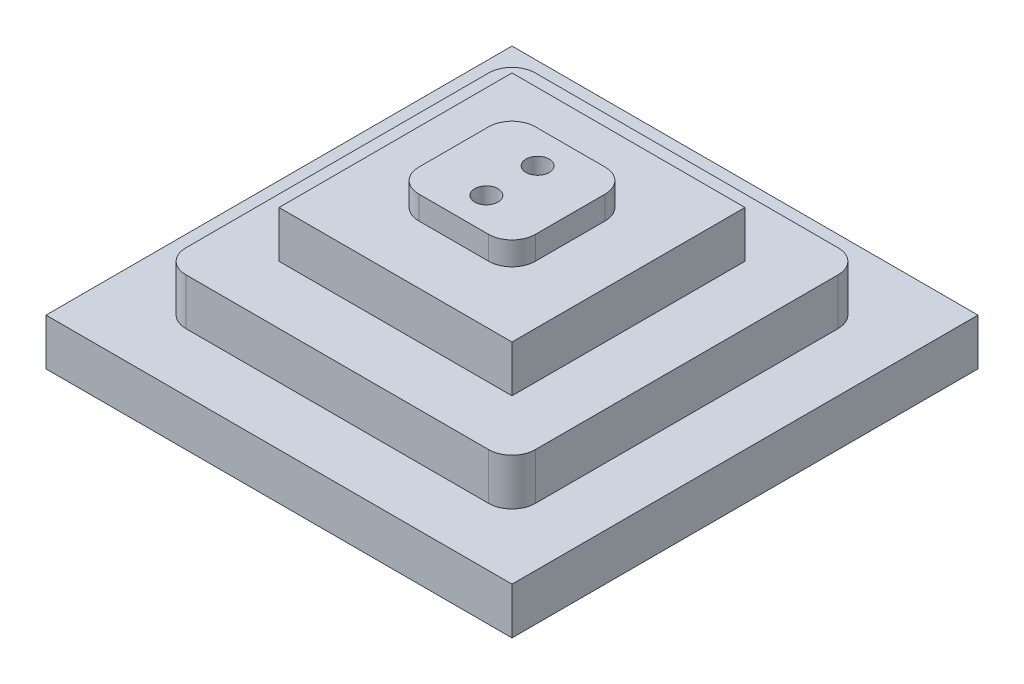
SolidWorks part; units mm, degrees
ref_plane "Front Plane" through (0, 0, 0) normal (0, 0, 1) x (1, 0, 0)
ref_plane "Top Plane" through (0, 0, 0) normal (0, 1, 0) x (1, 0, 0)
ref_plane "Right Plane" through (0, 0, 0) normal (1, 0, 0) x (0, 0, -1)
sketch "Sketch1" plane through (0, 0, 0) normal (0, 1, 0) x (1, 0, 0)
  line L1 (0, 0) -> (100, 0)
  line L2 (0, 0) -> (0, 100)
  line L3 (0, 100) -> (100, 100)
  line L4 (100, 0) -> (100, 100)
  dimension "D1" = 100
  dimension "D2" = 100
extrude "Boss-Extrude1" add sketch "Sketch1" along normal blind 10
sketch "Sketch2" plane through (0, 10, 0) normal (0, 1, 0) x (1, 0, 0)
  line L0 (0, 50) -> (100, 50) construction
  line L1 (0, 100) -> (0, 0) construction
  line L2 (100, 0) -> (100, 100) construction
  line L3 (50, 100) -> (50, 0) construction
  line L4 (100, 100) -> (0, 100) construction
  line L5 (0, 0) -> (100, 0) construction
  line L7 (87.5, 12.5) -> (12.5, 12.5)
  line L8 (87.5, 12.5) -> (87.5, 87.5)
  line L9 (87.5, 87.5) -> (12.5, 87.5)
  line L10 (12.5, 12.5) -> (12.5, 87.5)
  line L11 (87.5, 12.5) -> (12.5, 87.5) construction
  line L12 (87.5, 87.5) -> (12.5, 12.5) construction
  point P12 (50, 50)
  dimension "D1" = 75
  dimension "D2" = 75
extrude "Boss-Extrude2" add sketch "Sketch2" along normal blind 10
sketch "Sketch3" plane through (0, 20, 0) normal (0, 1, 0) x (1, 0, 0)
  line L0 (12.5, 50) -> (87.5, 50) construction
  line L1 (12.5, 87.5) -> (12.5, 12.5) construction
  line L2 (87.5, 12.5) -> (87.5, 87.5) construction
  line L3 (50, 87.5) -> (50, 12.5) construction
  line L4 (87.5, 87.5) -> (12.5, 87.5) construction
  line L5 (12.5, 12.5) -> (87.5, 12.5) construction
  line L7 (75, 25) -> (25, 25)
  line L8 (75, 25) -> (75, 75)
  line L9 (75, 75) -> (25, 75)
  line L10 (25, 25) -> (25, 75)
  line L11 (75, 25) -> (25, 75) construction
  line L12 (75, 75) -> (25, 25) construction
  point P12 (50, 50)
  dimension "D1" = 50
  dimension "D2" = 50
extrude "Boss-Extrude3" add sketch "Sketch3" along normal blind 10
sketch "Sketch4" plane through (0, 30, 0) normal (0, 1, 0) x (1, 0, 0)
  line L0 (25, 50) -> (75, 50) construction
  line L1 (25, 75) -> (25, 25) construction
  line L2 (75, 25) -> (75, 75) construction
  line L3 (50, 75) -> (50, 25) construction
  line L4 (75, 75) -> (25, 75) construction
  line L5 (25, 25) -> (75, 25) construction
  line L7 (62.5, 37.5) -> (37.5, 37.5)
  line L8 (62.5, 37.5) -> (62.5, 62.5)
  line L9 (62.5, 62.5) -> (37.5, 62.5)
  line L10 (37.5, 37.5) -> (37.5, 62.5)
  line L11 (62.5, 37.5) -> (37.5, 62.5) construction
  line L12 (62.5, 62.5) -> (37.5, 37.5) construction
  point P12 (50, 50)
  dimension "D1" = 25
  dimension "D2" = 25
extrude "Boss-Extrude4" add sketch "Sketch4" along normal blind 5
sketch "Sketch5" plane through (0, 35, 0) normal (0, 1, 0) x (1, 0, 0)
  line L0 (50, 62.5) -> (50, 37.5) construction
  line L1 (62.5, 62.5) -> (37.5, 62.5) construction
  line L2 (37.5, 37.5) -> (62.5, 37.5) construction
  line L3 (62.5, 62.5) -> (37.5, 62.5) construction
  circle A0 centre (50, 55.5) radius 2.5
  circle A1 centre (50, 44.5) radius 2.5
  point P12 (0, 0)
  point P13 (0, 0)
  dimension "D1" = 5
  dimension "D2" = 5
  dimension "D3" = 7
  dimension "D4" = 7
extrude "Cut-Extrude1" cut sketch "Sketch5" against normal blind 25
sketch "Sketch6" plane through (0, 10, 0) normal (0, 1, 0) x (1, 0, 0)
  circle A0 centre (50, 55.5) radius 1.5
  circle A1 centre (50, 44.5) radius 1.5
  dimension "D1" = 3
extrude "Cut-Extrude2" cut sketch "Sketch6" against normal blind 10
fillet "Fillet2" radius 5 8 edges at (12.5, 15, -87.5) (37.5, 32.5, -62.5) (37.5, 32.5, -37.5) (12.5, 15, -12.5) (87.5, 15, -12.5) (87.5, 15, -87.5) (62.5, 32.5, -62.5) (62.5, 32.5, -37.5)
